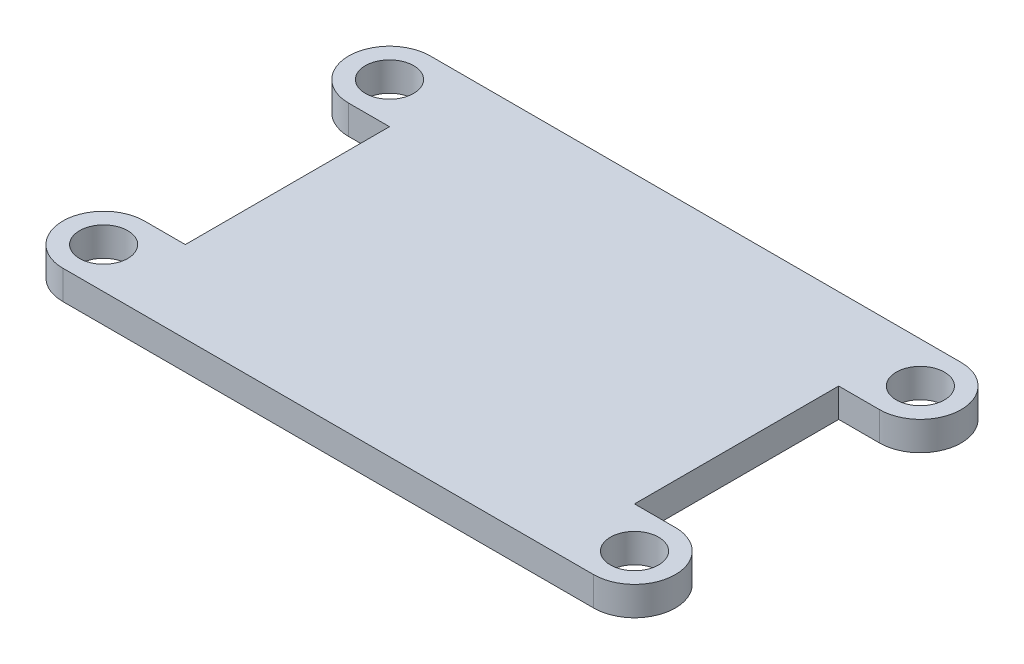
SolidWorks part; units mm, degrees
ref_plane "Alzado" through (0, 0, 0) normal (0, 0, 1) x (1, 0, 0)
ref_plane "Planta" through (0, 0, 0) normal (0, 1, 0) x (1, 0, 0)
ref_plane "Vista lateral" through (0, 0, 0) normal (1, 0, 0) x (0, 0, -1)
sketch "Croquis1" plane through (0, 0, 0) normal (0, 1, 0) x (1, 0, 0)
  line L0 (-13.97, 11.43) -> (-16.51, 11.43)
  line L1 (-13.97, -11.43) -> (13.97, -11.43)
  line L3 (-13.97, 11.43) -> (13.97, 11.43)
  line L4 (13.97, -6.35) -> (13.97, 6.35)
  line L5 (-13.97, -11.43) -> (13.97, 11.43) construction
  line L6 (-13.97, 11.43) -> (13.97, -11.43) construction
  line L7 (-13.97, -11.43) -> (-16.51, -11.43)
  line L8 (0, 0) -> (18.0733, 0) construction
  line L9 (-16.51, 6.35) -> (-13.97, 6.35)
  line L10 (-16.51, -6.35) -> (-13.97, -6.35)
  line L11 (-13.97, -6.35) -> (-13.97, 6.35)
  line L12 (13.97, -11.43) -> (16.51, -11.43)
  line L13 (16.51, -6.35) -> (13.97, -6.35)
  line L14 (13.97, 11.43) -> (16.51, 11.43)
  line L15 (16.51, 6.35) -> (13.97, 6.35)
  line L16 (0, 0) -> (0, -15.4444) construction
  arc A0 (-16.51, 11.43) -> (-16.51, 6.35) centre (-16.51, 8.89) ccw
  arc A1 (-16.51, -6.35) -> (-16.51, -11.43) centre (-16.51, -8.89) ccw
  arc A2 (16.51, -6.35) -> (16.51, -11.43) centre (16.51, -8.89) cw
  arc A3 (16.51, 11.43) -> (16.51, 6.35) centre (16.51, 8.89) cw
  circle A4 centre (-16.51, 8.89) radius 1.5
  circle A5 centre (16.51, 8.89) radius 1.5
  circle A6 centre (16.51, -8.89) radius 1.5
  circle A7 centre (-16.51, -8.89) radius 1.5
  point P0 (0, 0)
  dimension "D4" = 5.08
  dimension "D5" = 16.51
  dimension "D6" = 3
  dimension "D1" = 27.94
  dimension "D2" = 22.86
  dimension "D3" = 17.78
extrude "Saliente-Extruir1" add sketch "Croquis1" along normal blind 1.8
